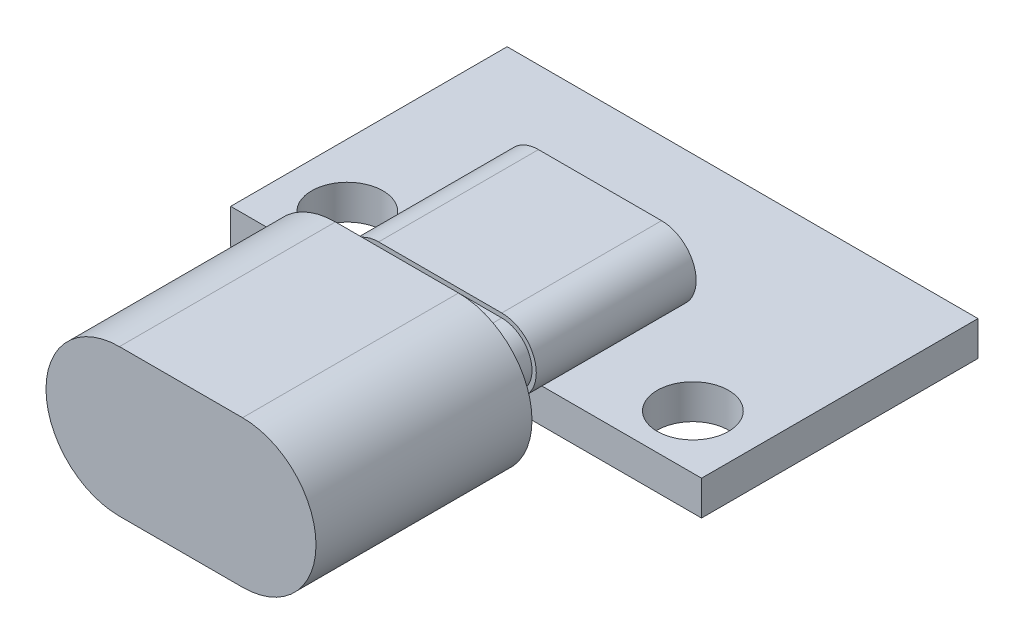
SolidWorks part; units mm, degrees
ref_plane "Front Plane" through (0, 0, 0) normal (0, 0, 1) x (1, 0, 0)
ref_plane "Top Plane" through (0, 0, 0) normal (0, 1, 0) x (1, 0, 0)
ref_plane "Right Plane" through (0, 0, 0) normal (1, 0, 0) x (0, 0, -1)
sketch "Sketch1" plane through (0, 0, 0) normal (0, 1, 0) x (1, 0, 0)
  line L1 (-10.9, -6.4) -> (10.9, -6.4)
  line L2 (-10.9, -6.4) -> (-10.9, 6.4)
  line L3 (-10.9, 6.4) -> (10.9, 6.4)
  line L4 (10.9, -6.4) -> (10.9, 6.4)
  line L5 (-10.9, -6.4) -> (10.9, 6.4) construction
  line L6 (-10.9, 6.4) -> (10.9, -6.4) construction
  point P0 (0, 0)
  dimension "D1" = 12.8
  dimension "D2" = 21.8
extrude "Boss-Extrude1" add sketch "Sketch1" along normal blind 1.6
sketch "Sketch2" plane through (0, 1.6, 0) normal (0, 1, 0) x (1, 0, 0)
  line L0 (-10.9, -3.9) -> (10.9, -3.9) construction
  line L1 (-10.9, 6.4) -> (-10.9, -6.4) construction
  line L2 (10.9, -6.4) -> (10.9, 6.4) construction
  line L3 (-10.9, -6.4) -> (10.9, -6.4) construction
  line L4 (-8, -3.9) -> (0, 0) construction
  line L5 (0, 0) -> (8, -3.9) construction
  circle A0 centre (-8, -3.9) radius 1.65
  circle A1 centre (8, -3.9) radius 1.65
  dimension "D1" = 3.3
  dimension "D2" = 16
  dimension "D3" = 2.5
extrude "Cut-Extrude1" cut sketch "Sketch2" against normal blind 1.6
ref_plane "Plane1" through (0, 0, 7.6) normal (0, 0, 1) x (1, 0, 0)
sketch "Sketch3" plane through (0, 0, 7.6) normal (0, 0, 1) x (1, 0, 0)
  line L0 (0, 0) -> (0, 3.2) construction
  line L1 (-2.85, 3.2) -> (2.85, 3.2) construction
  line L2 (-2.85, 4.8) -> (2.85, 4.8)
  line L3 (-2.85, 1.6) -> (2.85, 1.6)
  line L4 (-10.9, 1.6) -> (10.9, 1.6) construction
  arc A0 (-2.85, 4.8) -> (-2.85, 1.6) centre (-2.85, 3.2) ccw
  arc A1 (2.85, 1.6) -> (2.85, 4.8) centre (2.85, 3.2) ccw
  point P5 (0, 3.2)
  point P10 (0, 0)
  dimension "D1" = 8.9
  dimension "D2" = 3.2
extrude "Boss-Extrude2" add sketch "Sketch3" against normal blind 7.4
sketch "Sketch4" plane through (0, 0, 7.6) normal (0, 0, 1) x (1, 0, 0)
  line L4 (-2.85, 1.8) -> (2.85, 1.8)
  line L5 (2.85, 4.6) -> (-2.85, 4.6)
  line L6 (-2.85, 1.8) -> (2.85, 1.8)
  line L7 (2.85, 4.6) -> (-2.85, 4.6)
  arc A4 (-2.85, 4.6) -> (-2.85, 1.8) centre (-2.85, 3.2) ccw
  arc A5 (2.85, 1.8) -> (2.85, 4.6) centre (2.85, 3.2) ccw
  arc A6 (-2.85, 4.6) -> (-2.85, 1.8) centre (-2.85, 3.2) ccw
  arc A7 (2.85, 1.8) -> (2.85, 4.6) centre (2.85, 3.2) ccw
  dimension "D1" = 0.2
extrude "Boss-Extrude3" add sketch "Sketch4" along normal blind 2
sketch "Sketch5" plane through (0, 0, 9.6) normal (0, 0, 1) x (1, 0, 0)
  line L4 (-2.85, -0.2) -> (2.85, -0.2)
  line L5 (2.85, 6.6) -> (-2.85, 6.6)
  line L6 (-2.85, -0.2) -> (2.85, -0.2)
  line L7 (2.85, 6.6) -> (-2.85, 6.6)
  arc A4 (-2.85, 6.6) -> (-2.85, -0.2) centre (-2.85, 3.2) ccw
  arc A5 (2.85, -0.2) -> (2.85, 6.6) centre (2.85, 3.2) ccw
  arc A6 (-2.85, 6.6) -> (-2.85, -0.2) centre (-2.85, 3.2) ccw
  arc A7 (2.85, -0.2) -> (2.85, 6.6) centre (2.85, 3.2) ccw
  dimension "D3" = 12.5
  dimension "D2" = 6.8
  dimension "D1" = 2
extrude "Boss-Extrude4" add sketch "Sketch5" along normal blind 10
